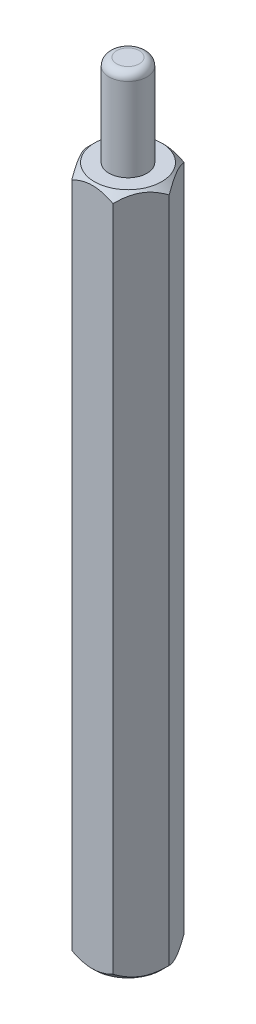
SolidWorks part; units mm, degrees
ref_plane "前视基准面" through (0, 0, 0) normal (0, 0, 1) x (1, 0, 0)
ref_plane "上视基准面" through (0, 0, 0) normal (0, 1, 0) x (1, 0, 0)
ref_plane "右视基准面" through (0, 0, 0) normal (1, 0, 0) x (0, 0, -1)
other "Configuration Table"
sketch "草图1" plane through (0, 0, 0) normal (0, 1, 0) x (1, 0, 0)
  line L1 (2.7135, 0) -> (1.3568, 2.35)
  line L2 (1.3568, 2.35) -> (-1.3568, 2.35)
  line L3 (-1.3568, 2.35) -> (-2.7135, 0)
  line L4 (-2.7135, 0) -> (-1.3568, -2.35)
  line L5 (-1.3568, -2.35) -> (1.3568, -2.35)
  line L6 (1.3568, -2.35) -> (2.7135, 0)
  circle A0 centre (0, 0) radius 2.35 construction
  dimension "D1" = 4.7
extrude "凸台-拉伸1" add sketch "草图1" along normal blind 45
sketch "草图2" plane through (0, 0, 0) normal (0, -1, 0) x (1, 0, 0)
  circle A0 centre (0, 0) radius 1.25
  dimension "D1" = 2.5
extrude "切除-拉伸1" cut sketch "草图2" against normal blind 10
sketch "草图4" plane through (0, 45, 0) normal (0, 1, 0) x (1, 0, 0)
  line L6 (1.3568, -2.35) -> (2.7135, 0)
  line L7 (2.7135, 0) -> (1.3568, 2.35)
  line L8 (1.3568, 2.35) -> (-1.3568, 2.35)
  line L9 (-1.3568, 2.35) -> (-2.7135, 0)
  line L10 (-2.7135, 0) -> (-1.3568, -2.35)
  line L11 (-1.3568, -2.35) -> (1.3568, -2.35)
  line L12 (1.3568, -2.35) -> (2.7135, 0)
  line L13 (2.7135, 0) -> (1.3568, 2.35)
  line L14 (1.3568, 2.35) -> (-1.3568, 2.35)
  line L15 (-1.3568, 2.35) -> (-2.7135, 0)
  line L16 (-2.7135, 0) -> (-1.3568, -2.35)
  line L17 (-1.3568, -2.35) -> (1.3568, -2.35)
  circle A1 centre (0, 0) radius 1.25
  circle A2 centre (0, 0) radius 1.25
  dimension "D1" = 0
  dimension "D2" = 0
extrude "凸台-拉伸2" add sketch "草图4" along normal blind 6 separate body contours A2
fillet "圆角1" radius 0.5 1 edges at (0, 51, 1.25)
sketch "草图7" plane through (0, 0, 0) normal (0, 0, 1) x (1, 0, 0)
  line L0 (-2.7135, 45) -> (-2.7135, 44.5)
  line L1 (-2.7135, 45) -> (-2.7135, 0) construction
  line L2 (-2.7135, 44.5) -> (-2.2135, 45)
  line L3 (-2.7135, 45) -> (-1.3568, 45) construction
  line L4 (-2.2135, 45) -> (-2.7135, 45)
  line L5 (0, 0) -> (1.4452, 0.3873)
  line L6 (0, 0) -> (0, 8.786) construction
  dimension "D1" = 0.5
  dimension "D2" = 0.5
revolve "切除-旋转4" cut sketch "草图7" angle 360 about L6
ref_plane "基准面1" through (0, 22.5, 0) normal (0, -1, 0) x (-1, 0, 0)
mirror "镜向1" about plane through (0, 22.5, 0) normal (0, -1, 0) of "切除-旋转4"
